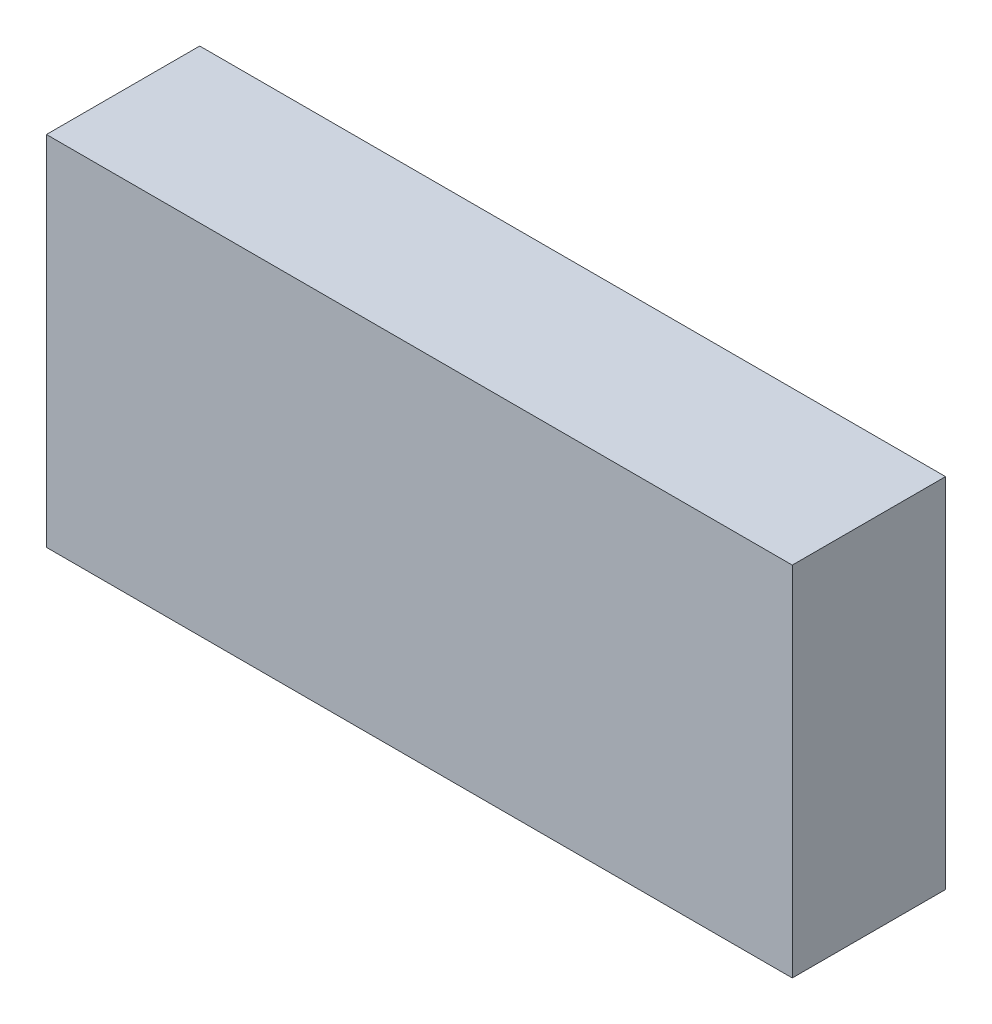
SolidWorks part; units mm, degrees
ref_plane "Plano frontal" through (0, 0, 0) normal (0, 0, 1) x (1, 0, 0)
ref_plane "Plano superior" through (0, 0, 0) normal (0, 1, 0) x (1, 0, 0)
ref_plane "Plano direito" through (0, 0, 0) normal (1, 0, 0) x (0, 0, -1)
sketch "Esboço1" plane through (0, 0, 0) normal (0, 0, 1) x (1, 0, 0)
  line L1 (-36.5, 17.5) -> (36.5, 17.5)
  line L2 (-36.5, 17.5) -> (-36.5, -17.5)
  line L3 (-36.5, -17.5) -> (36.5, -17.5)
  line L4 (36.5, 17.5) -> (36.5, -17.5)
  line L5 (-36.5, 17.5) -> (36.5, -17.5) construction
  line L6 (-36.5, -17.5) -> (36.5, 17.5) construction
  point P0 (0, 0)
  dimension "D1" = 73
  dimension "D2" = 35
extrude "Ressalto-extrusão1" add sketch "Esboço1" along normal blind 15
